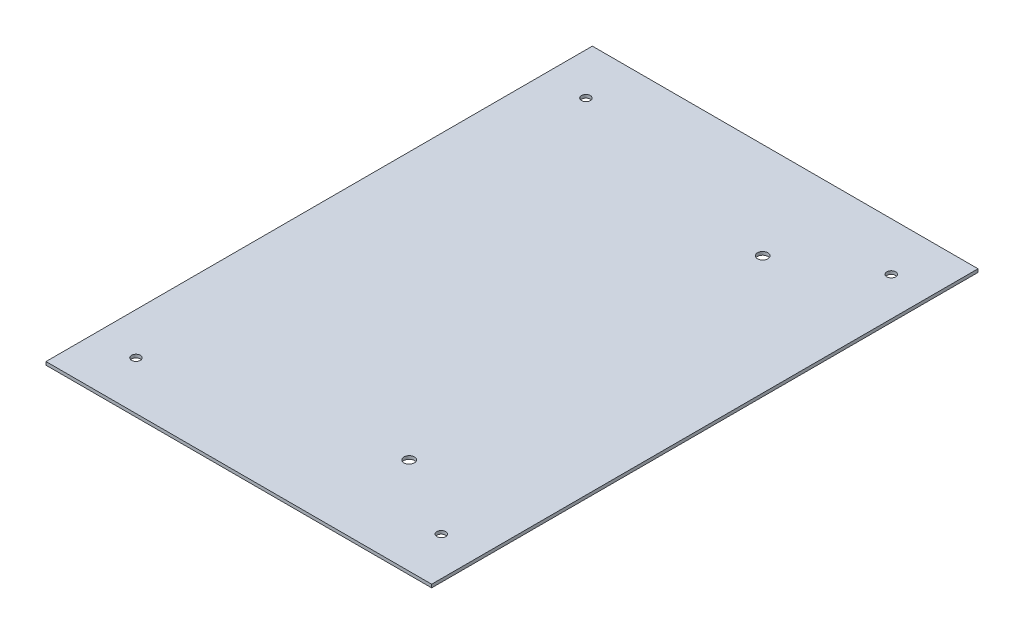
SolidWorks part; units mm, degrees
ref_plane "Plan1" through (0, 0, 0) normal (0, 0, 1) x (1, 0, 0)
ref_plane "Plan2" through (0, 0, 0) normal (0, 1, 0) x (1, 0, 0)
ref_plane "Plan3" through (0, 0, 0) normal (1, 0, 0) x (0, 0, -1)
sketch "Esquisse1" plane through (0, 0, 0) normal (0, 0, 1) x (1, 0, 0)
  line L0 (0, 0) -> (240, 0)
  line L1 (0, 0) -> (0, 2)
  line L2 (240, 2) -> (0, 2)
  line L3 (240, 2) -> (240, 0)
  dimension "D1" = 240
  dimension "D2" = 2
extrude "Base-Extrusion" add sketch "Esquisse1" along normal blind 340
sketch "Esquisse2" plane through (0, 2, 0) normal (0, 1, 0) x (-1, 0, 0)
  line L1 (-240, 0) -> (0, 0) construction
  line L2 (-240, 340) -> (-240, 0) construction
  circle A0 centre (-216, 30) radius 2.75
  dimension "D1" = 24
  dimension "D2" = 30
  dimension "D3" = 5.5
extrude "Enlèv. mat.-Extru.1" cut sketch "Esquisse2" against normal through all
pattern_linear "Répétition linéaire1" count 2 spacing 190 count 2 spacing 280
sketch "Esquisse3" plane through (0, 2, 0) normal (0, 1, 0) x (-1, 0, 0)
  line L0 (-166, 330) -> (-166, 20) construction
  line L1 (-240, 340) -> (-240, 0) construction
  line L2 (-240, 0) -> (0, 0) construction
  line L3 (-240, 340) -> (0, 340) construction
  circle A0 centre (-166, 280) radius 3.25
  circle A1 centre (-166, 60) radius 3.25
  dimension "D2" = 6.5
  dimension "D3" = 60
  dimension "D4" = 60
  dimension "D1" = 74
extrude "Enlèv. mat.-Extru.2" cut sketch "Esquisse3" against normal through all
